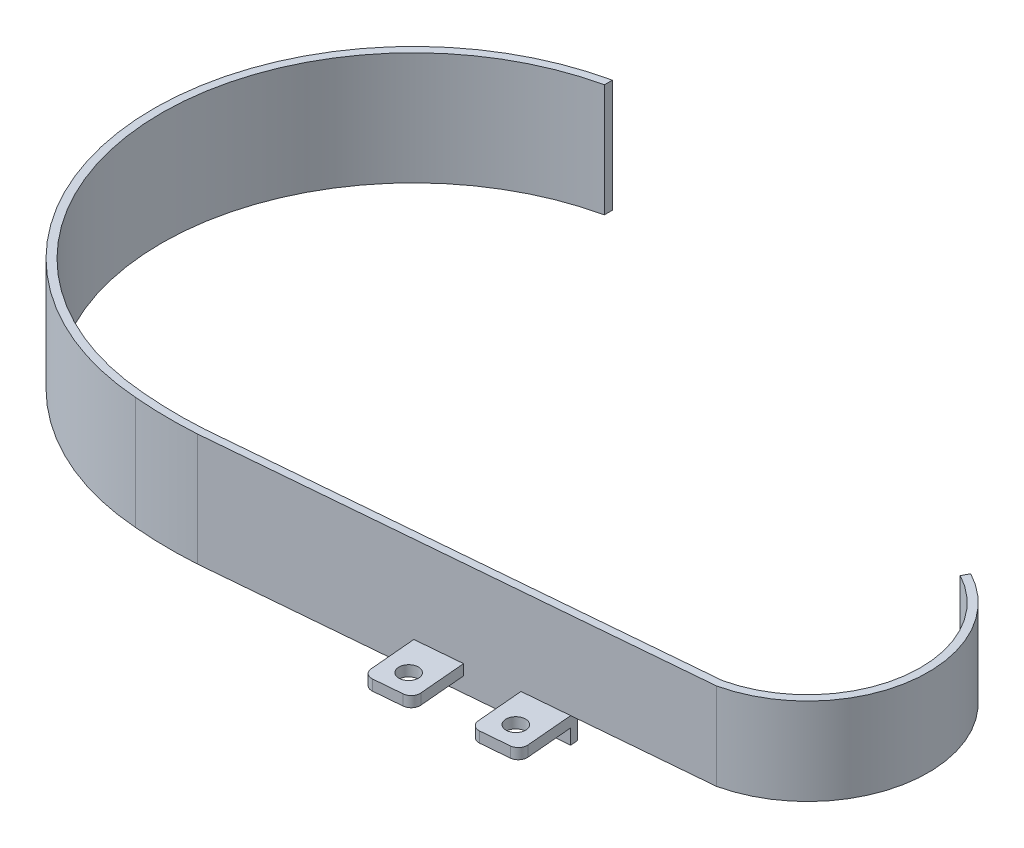
SolidWorks part; units mm, degrees
material "Alloy Steel"
ref_plane "X-Y Datum" through (0, 0, 0) normal (0, 0, 1) x (1, 0, 0)
ref_plane "X-Z Datum" through (0, 0, 0) normal (0, 1, 0) x (1, 0, 0)
ref_plane "Y-Z Datum" through (0, 0, 0) normal (1, 0, 0) x (0, 0, -1)
sketch "Sketch1" plane through (0, 0, 0) normal (0, 1, 0) x (1, 0, 0)
  line L3 (196.8894, -0.4253) -> (198.2012, 2.0416)
  line L5 (186.8392, -75.8168) -> (-240.3609, -168.11) construction
  line L6 (187.4438, -78.5446) -> (-240.7639, -171.0555) construction
  line L13 (187.4438, -78.5446) -> (15.7339, -93.3972)
  line L14 (186.8392, -75.8168) -> (15.7339, -90.617)
  line L15 (-19.7919, 88.4037) -> (-19.7919, 91.2648)
  arc A1 (140.5399, -43.7003) -> (140.3596, -29.7706) centre (177.8394, -36.2514) ccw construction
  circle A2 centre (177.8394, -36.2514) radius 38.036 construction
  circle A5 centre (0, 0) radius 78.9148 construction
  arc A7 (186.8392, -75.8168) -> (196.8894, -0.4253) centre (177.8394, -36.2514) ccw
  arc A8 (138.0491, -44.1977) -> (196.8894, -0.4253) centre (177.8394, -36.2514) ccw construction
  arc A14 (140.5399, -43.7003) -> (195.6969, -2.668) centre (177.8394, -36.2514) ccw construction
  arc A15 (187.4438, -78.5446) -> (198.2012, 2.0416) centre (177.8394, -36.2514) ccw
  arc A16 (-240.3609, -168.11) -> (-57.1477, -125.3744) centre (-173.2452, -41.7464) cw construction
  arc A17 (-240.7639, -171.0555) -> (-56.2783, -128.915) centre (-173.2452, -41.7464) cw construction
  arc A21 (-0.0984, 91.6924) -> (-57.1477, -125.3744) centre (-5.4947, -22.9196) ccw construction
  arc A22 (0.033, 94.4833) -> (-56.2783, -128.915) centre (-5.4947, -22.9196) ccw construction
  circle A40 centre (0, 0) radius 78.9148 construction
  circle A41 centre (177.8394, -36.2514) radius 24.535 construction
  circle A42 centre (177.8394, -36.2514) radius 27.5082 construction
  circle A43 centre (0, 0) radius 82.9722 construction
  circle A44 centre (0, 0) radius 90.5922 construction
  circle A45 centre (0, 0) radius 93.3862 construction
  arc A46 (15.7339, -93.3972) -> (-6.8573, -93.1341) centre (6.1317, 52.1304) cw
  arc A47 (15.7339, -90.617) -> (-6.8573, -90.3323) centre (6.2711, 54.9197) cw
  arc A48 (-6.8573, -90.3323) -> (-19.7919, 88.4037) centre (0, 0) cw
  arc A49 (-6.8573, -93.1341) -> (-19.7919, 91.2648) centre (0, 0) cw
  dimension "D5" = 76.072
  dimension "D6" = 2.794
  dimension "D3" = 36.2514
  dimension "D12" = 165.9443
  dimension "D9" = 157.8295
  dimension "D11" = 177.8394
  dimension "D13" = 145.844
  dimension "D17" = 90.617
  dimension "D19" = 55.0164
  dimension "D15" = 172.3511
  dimension "D18" = 49.07
  dimension "D4" = 7.62
  dimension "D8" = 19.05
  dimension "D10" = 8.9997
  dimension "D14" = 42.2932
  dimension "D16" = 19.7919
  dimension "D2" = 2.54
  dimension "D7" = 2.794
extrude "Boss-Extrude1" add sketch "Sketch1" along normal blind 18.161 and the other way blind 22.3266 contours A7 L3 A15 L13 A46 A49 L15 A48 A47 L14
sketch "Sketch2" plane through (8.1355, 0, 94.0544) normal (0.0862, 0, 0.9963) x (0.9963, 0, -0.0862)
  line L0 (131.5509, -22.3266) -> (131.5509, -13.1068)
  line L1 (131.5509, -13.1068) -> (133.5829, -13.1068)
  line L2 (230.7778, -13.1068) -> (230.7778, -22.3266)
  line L3 (230.7778, -22.3266) -> (179.9778, -22.3266)
  line L4 (179.9778, -22.3266) -> (131.5509, -22.3266)
  line L5 (134.9432, -5.5294) -> (122.7232, -5.5294)
  line L6 (133.5829, -13.1068) -> (230.7778, -13.1068)
  line M7 (179.9778, -22.3266) -> (179.9778, 18.161)
  line M10 (7.6268, -22.3266) -> (179.9778, -22.3266)
  dimension "D1" = 97.1949
  dimension "D2" = 99.2269
  dimension "D3" = 9.2198
extrude "Cut-Extrude1" cut sketch "Sketch2" against normal through all contours L6 L1 L0 M10 M7 | L6 L3 L2 M7
sketch "Sketch3" plane through (8.1355, 0, 94.0544) normal (0.0862, 0, 0.9963) x (0.9963, 0, -0.0862)
  line L1 (131.5509, -13.1068) -> (115.0409, -13.1068)
  line L2 (131.5509, -13.1068) -> (131.5509, -16.9168)
  line L3 (131.5509, -16.9168) -> (115.0409, -16.9168)
  line L4 (115.0409, -13.1068) -> (115.0409, -16.9168)
  line L5 (95.9909, -13.1068) -> (79.4809, -13.1068)
  line L6 (95.9909, -13.1068) -> (95.9909, -16.9168)
  line L7 (95.9909, -16.9168) -> (79.4809, -16.9168)
  line L8 (79.4809, -13.1068) -> (79.4809, -16.9168)
  dimension "D1" = 16.51
  dimension "D2" = 3.81
  dimension "D3" = 19.05
extrude "Boss-Extrude2" add sketch "Sketch3" along normal blind 20.066
fillet "Fillet1" radius 3.175 4 edges at (89.0499, -15.0118, 107.1964) (105.4985, -15.0118, 105.7736) (140.9262, -15.0118, 102.7092) (124.4776, -15.0118, 104.132)
sketch "Sketch6" plane through (0, 0, 0) normal (0, 1, 0) x (1, 0, 0)
  line L1 (105.2249, -102.6105) -> (103.7693, -85.7823) construction
  line L5 (140.6526, -99.546) -> (139.197, -82.7179) construction
  line L6 (139.197, -82.7179) -> (122.7484, -84.1406) construction
  line L7 (103.7693, -85.7823) -> (87.3207, -87.2051) construction
  circle A1 centre (96.7067, -98.4497) radius 3.5
  circle A3 centre (132.1344, -95.3853) radius 3.5
  dimension "D3" = 7
  dimension "D1" = 8.128
  dimension "D2" = 12.0117
  dimension "D4" = 12.0117
  dimension "D5" = 8.128
extrude "Cut-Extrude2" cut sketch "Sketch6" against normal through all
sketch "Bend-Lines1" [suppressed] plane through (0, 0, 0) normal (0, 1, 0) x (1, 0, 0)
sketch "Bounding-Box1" [suppressed] plane through (0, 0, 0) normal (0, 1, 0) x (1, 0, 0)
